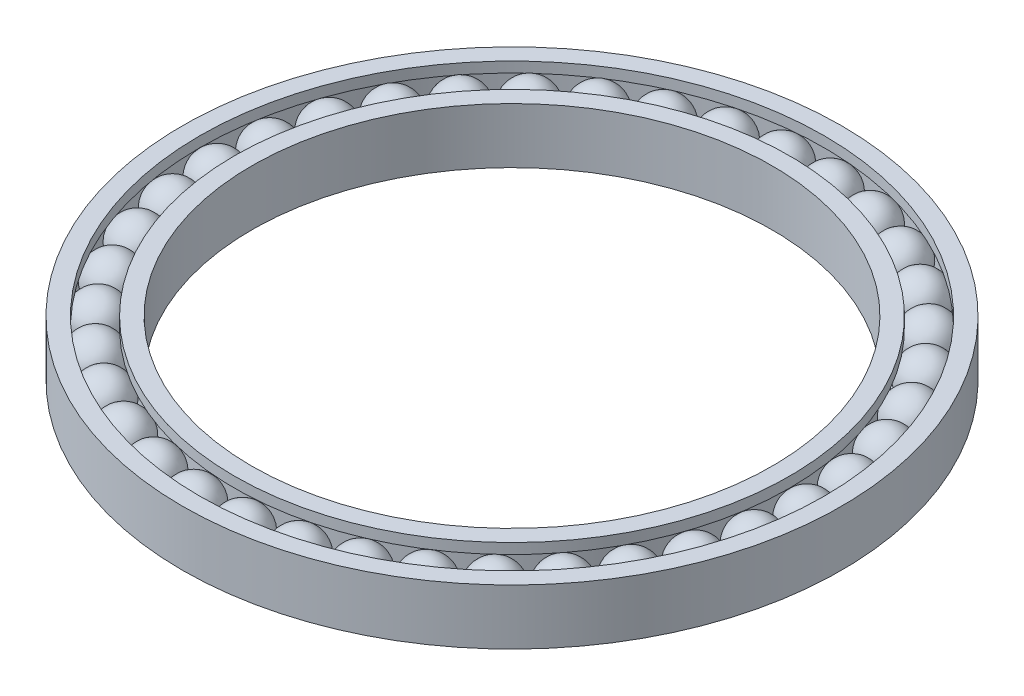
SolidWorks part; units mm, degrees
ref_plane "Front Plane" through (0, 0, 0) normal (0, 0, 1) x (1, 0, 0)
ref_plane "Top Plane" through (0, 0, 0) normal (0, 1, 0) x (1, 0, 0)
ref_plane "Right Plane" through (0, 0, 0) normal (1, 0, 0) x (0, 0, -1)
sketch "Sketch2" plane through (0, 0, 0) normal (0, 1, 0) x (1, 0, 0)
  circle A0 centre (0, 0) radius 47.5
  circle A1 centre (0, 0) radius 45
  dimension "D1" = 95
  dimension "D2" = 90
extrude "Boss-Extrude1" add sketch "Sketch2" along normal blind 8 from offset 3
sketch "Sketch5" plane through (0, 0, 0) normal (0, 1, 0) x (1, 0, 0)
  circle A0 centre (0, 0) radius 37.5
  circle A1 centre (0, 0) radius 40
  dimension "D1" = 75
  dimension "D2" = 80
extrude "Boss-Extrude2" add sketch "Sketch5" along normal blind 8 from offset 3 separate body
sketch "Sketch3" plane through (0, 0, 0) normal (0, 0, 1) x (1, 0, 0)
  line L0 (0, 10.5) -> (0, 2.5) construction
  line L3 (45, 11) -> (-45, 11) construction
  line L4 (-38.75, 9.5) -> (-46.25, 9.5)
  line L5 (-38.75, 9.5) -> (-38.75, 4.5)
  line L6 (-38.75, 4.5) -> (-46.25, 4.5)
  line L8 (-46.25, 4.5) -> (-46.25, 9.5)
  line L11 (0, 9) -> (0, 4)
  line L12 (0, 9) -> (0, 4)
  point P6 (0, 6.5)
  dimension "D1" = 5
  dimension "D2" = 38.75
  dimension "D3" = 46.25
  dimension "D4" = 1.5
revolve "Cut-Revolve1" cut sketch "Sketch3" angle 360 about L0
sketch "Sketch6" plane through (0, 0, 0) normal (0, 0, 1) x (1, 0, 0)
  line L0 (41.233, 9) -> (41.233, 4.5) construction
  line L2 (40, 4.5) -> (-40, 4.5) construction
  line L3 (42.5017, 7.0212) -> (41.233, 7.0212) construction
  line L4 (9.5, 11) -> (75.5035, 11) construction
  line L5 (40, 11) -> (-40, 11) construction
  line L8 (42.5017, 11) -> (42.5017, 7.0212) construction
  line L9 (42.5017, 8.4496) -> (42.5017, 7.0212)
  line L10 (42.5017, 8.4496) -> (41.233, 8.4496) construction
  line L12 (42.5017, 10.5212) -> (42.5017, 3.5212)
  line L13 (39.3065, 8.4496) -> (38.7226, 8.4496) construction
  line L14 (39.0017, 7.0212) -> (15.2063, 7.0212) construction
  arc A0 (39.3065, 8.4496) -> (39.0017, 7.0212) centre (42.5017, 7.0212) ccw
  arc A1 (41.233, 3.7592) -> (41.233, 10.2831) centre (42.5017, 7.0212) ccw
  arc A3 (41.233, 3.7592) -> (41.233, 10.2831) centre (42.5017, 7.0212) ccw
  dimension "D1" = 7
revolve "Revolve4" add sketch "Sketch6" angle 360 about L8
pattern_circular "CirPattern4" count 38 over 360 about axis through (0, 0, 0) along (0, 1, 0) of bodies 346 106 226
